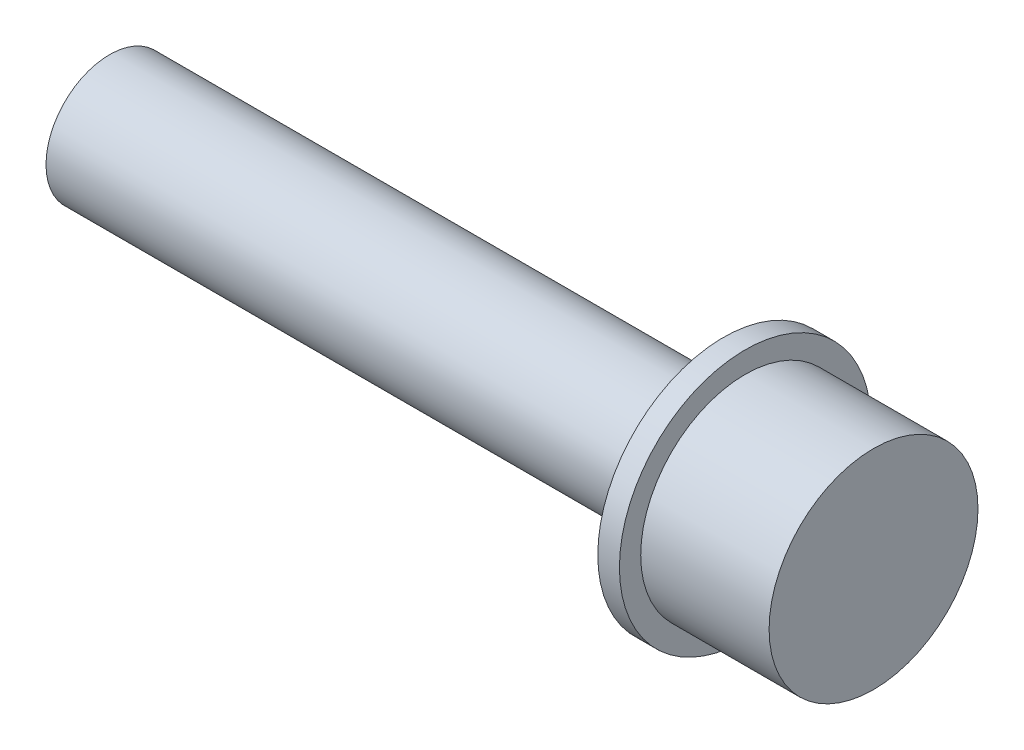
SolidWorks part; units mm, degrees
ref_plane "Front Plane" through (0, 0, 0) normal (0, 0, 1) x (1, 0, 0)
ref_plane "Top Plane" through (0, 0, 0) normal (0, 1, 0) x (1, 0, 0)
ref_plane "Right Plane" through (0, 0, 0) normal (1, 0, 0) x (0, 0, -1)
other "Configuration Table"
sketch "Sketch1" plane through (0, 0, 0) normal (1, 0, 0) x (0, 0, -1)
  circle A0 centre (0, 0) radius 4.93
  dimension "D1" = 9.86
extrude "Boss-Extrude1" add sketch "Sketch1" along normal blind 6.06
sketch "Sketch2" plane through (0, 0, 0) normal (-1, 0, 0) x (0, 0, 1)
  circle A0 centre (0, 0) radius 3
  dimension "D1" = 6
extrude "Boss-Extrude2" add sketch "Sketch2" along normal blind 30
sketch "Sketch3" plane through (0, 0, 0) normal (-1, 0, 0) x (0, 0, 1)
  circle A0 centre (0, 0) radius 5.935
  dimension "D1" = 11.87
extrude "Boss-Extrude3" add sketch "Sketch3" along normal blind 1.02
